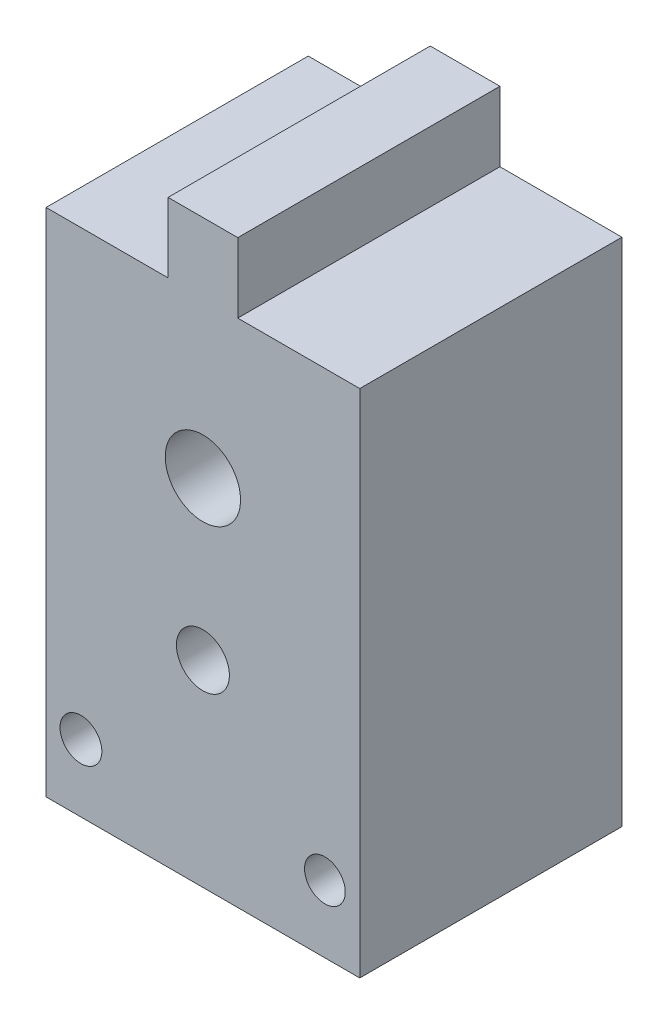
SolidWorks part; units mm, degrees
ref_plane "Front Plane" through (0, 0, 0) normal (0, 0, 1) x (1, 0, 0)
ref_plane "Top Plane" through (0, 0, 0) normal (0, 1, 0) x (1, 0, 0)
ref_plane "Right Plane" through (0, 0, 0) normal (1, 0, 0) x (0, 0, -1)
sketch "Sketch1" plane through (0, 0, 0) normal (0, 0, 1) x (1, 0, 0)
  line L0 (-2.4957, 15.781) -> (-11.2307, 15.781)
  line L1 (-11.2307, 15.781) -> (-11.2307, -20.7724)
  line L2 (-11.2307, -20.7724) -> (11.2307, -20.7724)
  line L3 (11.2307, -20.7724) -> (11.2307, 15.781)
  line L4 (11.2307, 15.781) -> (2.4957, 15.781)
  line L5 (2.4957, 15.781) -> (2.4957, 20.7724)
  line L6 (2.4957, 20.7724) -> (-2.4957, 20.7724)
  line L7 (-2.4957, 20.7724) -> (-2.4957, 15.781)
  circle A0 centre (0, -6.6805) radius 1.8967
  circle A1 centre (8.735, -15.9645) radius 1.4583
  circle A2 centre (-8.735, -15.9645) radius 1.4974
  circle A3 centre (0, 4.6002) radius 2.6954
  point P18 (0, 20.7724)
  dimension "D1" = 17.47
  dimension "D6" = 9.2841
  dimension "D7" = 11.2806
  dimension "D8" = 4.8079
  dimension "D2" = 22.4614
  dimension "D3" = 36.5534
  dimension "D4" = 4.9914
  dimension "D5" = 4.9914
extrude "Boss-Extrude1" add sketch "Sketch1" along normal mid plane 18.773
sketch "Sketch2" plane through (0, 0, 0) normal (0, 0, 1) x (1, 0, 0)
  line L2 (2.0092, 6.3968) -> (-2.0092, 6.3968)
  line L3 (-2.0092, 2.8035) -> (2.0092, 2.8035)
  circle A3 centre (0, 4.6002) radius 2.6954 construction
  arc A4 (-2.0092, 2.8035) -> (-2.0092, 6.3968) centre (0, 4.6002) cw
  arc A5 (2.0092, 6.3968) -> (2.0092, 2.8035) centre (0, 4.6002) cw
  circle A6 centre (0, 4.6002) radius 2.6954 construction
  dimension "D1" = 3.5933
  dimension "D2" = 5.3907
equation "\"motor_thiccness\"=18.773"
equation "\"D1@Boss-Extrude1\"=\"motor_thiccness\""
equation "\"axis\"=18.25"
